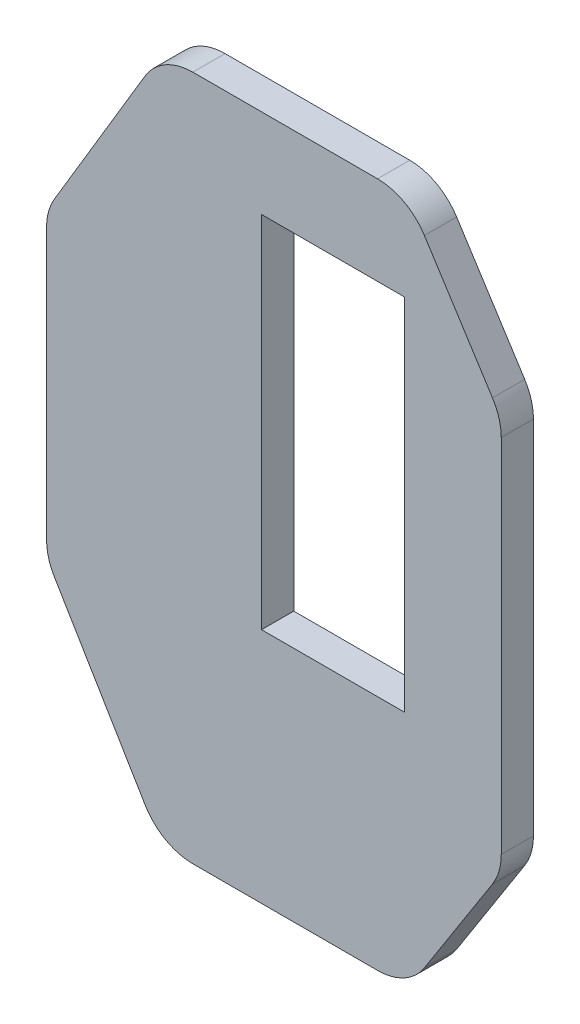
SolidWorks part; units mm, degrees
ref_plane "正面" through (0, 0, 0) normal (0, 0, 1) x (1, 0, 0)
ref_plane "平面" through (0, 0, 0) normal (0, 1, 0) x (1, 0, 0)
ref_plane "右側面" through (0, 0, 0) normal (1, 0, 0) x (0, 0, -1)
sketch "ｽｹｯﾁ1" plane through (0, 0, 0) normal (0, 0, 1) x (1, 0, 0)
  line L10 (-9.8498, 20.9) -> (-23.1501, 20.9)
  line L11 (-9.8498, -12.6) -> (-9.8498, 20.9)
  line L12 (-23.1501, -12.6) -> (-9.8498, -12.6)
  line L13 (-23.1501, 20.9) -> (-23.1501, -12.6)
  line L26 (-1.6343, 16.8554) -> (-7.9776, 26.788)
  line L27 (-0.82, -19.5742) -> (-0.82, 14.0673)
  line L28 (-7.9776, -32.2949) -> (-1.6343, -22.3622)
  line L29 (-29.5491, -34.6868) -> (-12.3433, -34.6868)
  line L30 (-42.4483, -17.9991) -> (-33.9974, -32.1612)
  line L31 (-43.18, 9.8379) -> (-43.18, -15.3447)
  line L32 (-33.9974, 26.6544) -> (-42.4483, 12.4923)
  line L33 (-12.3433, 29.18) -> (-29.5491, 29.18)
  arc A16 (-0.82, 14.0673) -> (-1.6343, 16.8554) centre (-6, 14.0673) ccw
  arc A17 (-1.6343, -22.3622) -> (-0.82, -19.5742) centre (-6, -19.5742) ccw
  arc A18 (-12.3433, -34.6868) -> (-7.9776, -32.2949) centre (-12.3433, -29.5068) ccw
  arc A19 (-33.9974, -32.1612) -> (-29.5491, -34.6868) centre (-29.5491, -29.5068) ccw
  arc A20 (-43.18, -15.3447) -> (-42.4483, -17.9991) centre (-38, -15.3447) ccw
  arc A21 (-42.4483, 12.4923) -> (-43.18, 9.8379) centre (-38, 9.8379) ccw
  arc A22 (-29.5491, 29.18) -> (-33.9974, 26.6544) centre (-29.5491, 24) ccw
  arc A23 (-7.9776, 26.788) -> (-12.3433, 29.18) centre (-12.3433, 24) ccw
extrude "ﾎﾞｽ - 押し出し1" add sketch "ｽｹｯﾁ1" along normal blind 3
